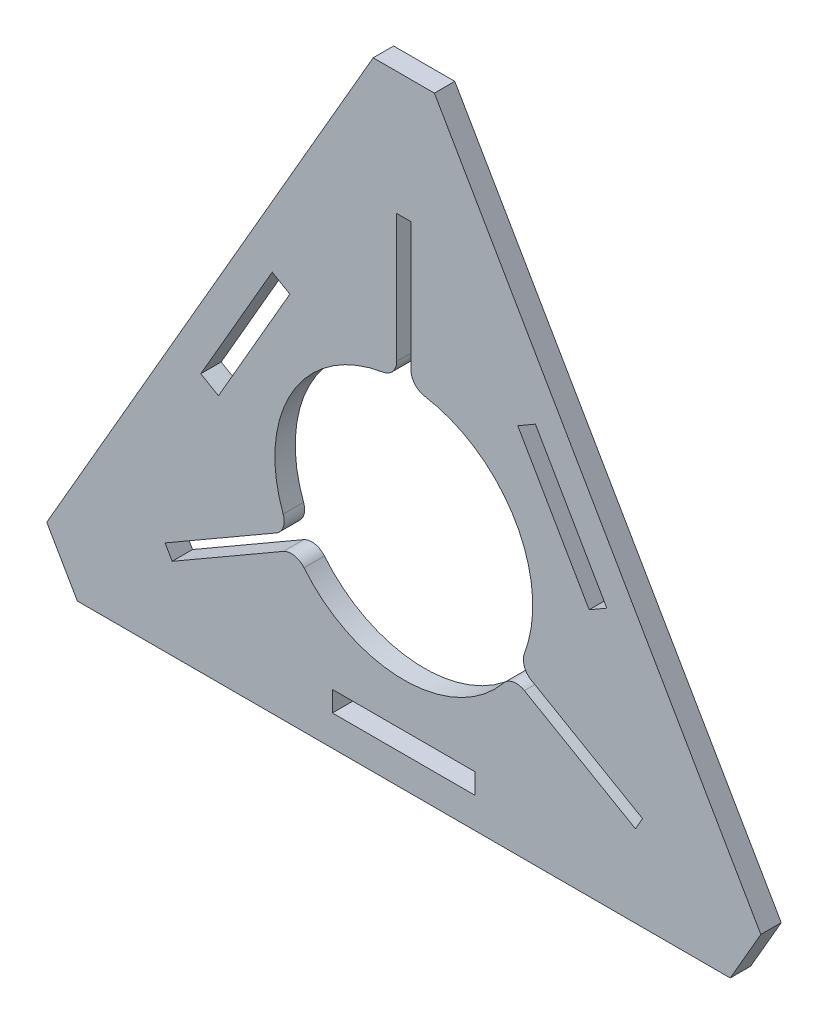
SolidWorks part; units mm, degrees
ref_plane "Front Plane" through (0, 0, 0) normal (0, 0, 1) x (1, 0, 0)
ref_plane "Top Plane" through (0, 0, 0) normal (0, 1, 0) x (1, 0, 0)
ref_plane "Right Plane" through (0, 0, 0) normal (1, 0, 0) x (0, 0, -1)
sketch "Sketch1" plane through (0, 0, 0) normal (0, 0, 1) x (1, 0, 0)
  line L0 (0, 0) -> (0, 146.6407) construction
  line L1 (-2.2225, 84.5204) -> (2.2225, 84.5204)
  line L2 (-2.2225, 84.5204) -> (-2.2225, 44.6184)
  line L4 (2.2225, 84.5204) -> (2.2225, 44.6184)
  line L5 (-2.2225, 84.5204) -> (2.2225, 40.0704) construction
  line L6 (-2.2225, 40.0704) -> (2.2225, 84.5204) construction
  line L7 (74.3081, -40.3355) -> (72.0856, -44.1849)
  line L8 (72.0856, -44.1849) -> (37.5294, -24.2339)
  line L9 (74.3081, -40.3355) -> (39.7519, -20.3844)
  line L10 (74.3081, -40.3355) -> (33.5907, -21.9599) construction
  line L11 (0, 0) -> (126.9945, -73.3203) construction
  line L12 (35.8132, -18.1105) -> (72.0856, -44.1849) construction
  line L13 (-72.0856, -44.1849) -> (-74.3081, -40.3355)
  line L14 (-74.3081, -40.3355) -> (-39.7519, -20.3844)
  line L15 (-72.0856, -44.1849) -> (-37.5294, -24.2339)
  line L16 (-72.0856, -44.1849) -> (-35.8132, -18.1105) construction
  line L17 (0, 0) -> (-126.9945, -73.3203) construction
  line L18 (-33.5907, -21.9599) -> (-74.3081, -40.3355) construction
  line L19 (0, -69.6573) -> (101.6, -69.6573)
  line L21 (0, -69.6573) -> (-101.6, -69.6573)
  line L22 (0, 0) -> (0, -69.6573) construction
  line L23 (-111.125, -53.1595) -> (-9.525, 122.8168)
  line L24 (-9.525, 122.8168) -> (9.525, 122.8168)
  line L25 (-111.125, -53.1595) -> (-101.6, -69.6573)
  line L26 (101.6, -69.6573) -> (111.125, -53.1595)
  line L27 (111.125, -53.1595) -> (9.525, 122.8168)
  line L28 (0, 0) -> (124.9753, 72.1545) construction
  line L29 (-22.225, -53.7823) -> (22.225, -53.7823)
  line L30 (-22.225, -53.7823) -> (-22.225, -60.1323)
  line L31 (-22.225, -60.1323) -> (22.225, -60.1323)
  line L32 (22.225, -53.7823) -> (22.225, -60.1323)
  line L33 (-22.225, -53.7823) -> (22.225, -60.1323) construction
  line L34 (-22.225, -60.1323) -> (22.225, -53.7823) construction
  line L35 (0, 0) -> (-93.1537, 53.7823) construction
  line L36 (-63.1886, 10.8187) -> (-40.9636, 49.3136)
  line L37 (-40.9636, 49.3136) -> (-35.4643, 46.1386)
  line L38 (-35.4643, 46.1386) -> (-57.6893, 7.6437)
  line L39 (-57.6893, 7.6437) -> (-63.1886, 10.8187)
  line L40 (-60.439, 9.2312) -> (-38.214, 47.7261) construction
  line L41 (40.9636, 49.3136) -> (35.4643, 46.1386)
  line L42 (63.1886, 10.8187) -> (40.9636, 49.3136)
  line L43 (57.6893, 7.6437) -> (63.1886, 10.8187)
  line L44 (35.4643, 46.1386) -> (57.6893, 7.6437)
  arc A0 (-6.482, 39.6051) -> (-37.54, -14.189) centre (0, 0) ccw
  arc A1 (-31.058, -25.4161) -> (31.058, -25.4161) centre (0, 0) ccw
  arc A2 (37.54, -14.189) -> (6.482, 39.6051) centre (0, 0) ccw
  arc A3 (-37.54, -14.189) -> (-39.7519, -20.3844) centre (-42.2919, -15.985) cw
  arc A4 (-37.5294, -24.2339) -> (-31.058, -25.4161) centre (-34.9894, -28.6333) cw
  arc A5 (31.058, -25.4161) -> (37.5294, -24.2339) centre (34.9894, -28.6333) cw
  arc A6 (37.54, -14.189) -> (39.7519, -20.3844) centre (42.2919, -15.985) ccw
  arc A7 (6.482, 39.6051) -> (2.2225, 44.6184) centre (7.3025, 44.6184) cw
  arc A8 (-6.482, 39.6051) -> (-2.2225, 44.6184) centre (-7.3025, 44.6184) ccw
  point P3 (0, 62.2954)
  point P20 (0, 0)
  point P38 (106.3625, -61.4084)
  point P45 (0, 122.8168)
  point P46 (-106.3625, -61.4084)
  point P47 (0, -56.9573)
  point P52 (-60.325, 34.8287)
  point P55 (60.325, 34.8287)
  point P58 (-46.5768, 26.8912)
  dimension "D1" = 80.264
  dimension "D5" = 5.08
  dimension "D2" = 44.45
  dimension "D3" = 4.445
  dimension "D6" = 19.05
  dimension "D7" = 203.2
  dimension "D8" = 101.6
  dimension "D9" = 6.35
  dimension "D10" = 19.05
  dimension "D11" = 19.05
  dimension "D12" = 44.45
  dimension "D13" = 12.7
  dimension "D14" = 6.35
  dimension "D15" = 44.45
  dimension "D16" = 12.7
  dimension "D4" = 3
extrude "Boss-Extrude1" add sketch "Sketch1" along normal blind 6.35
